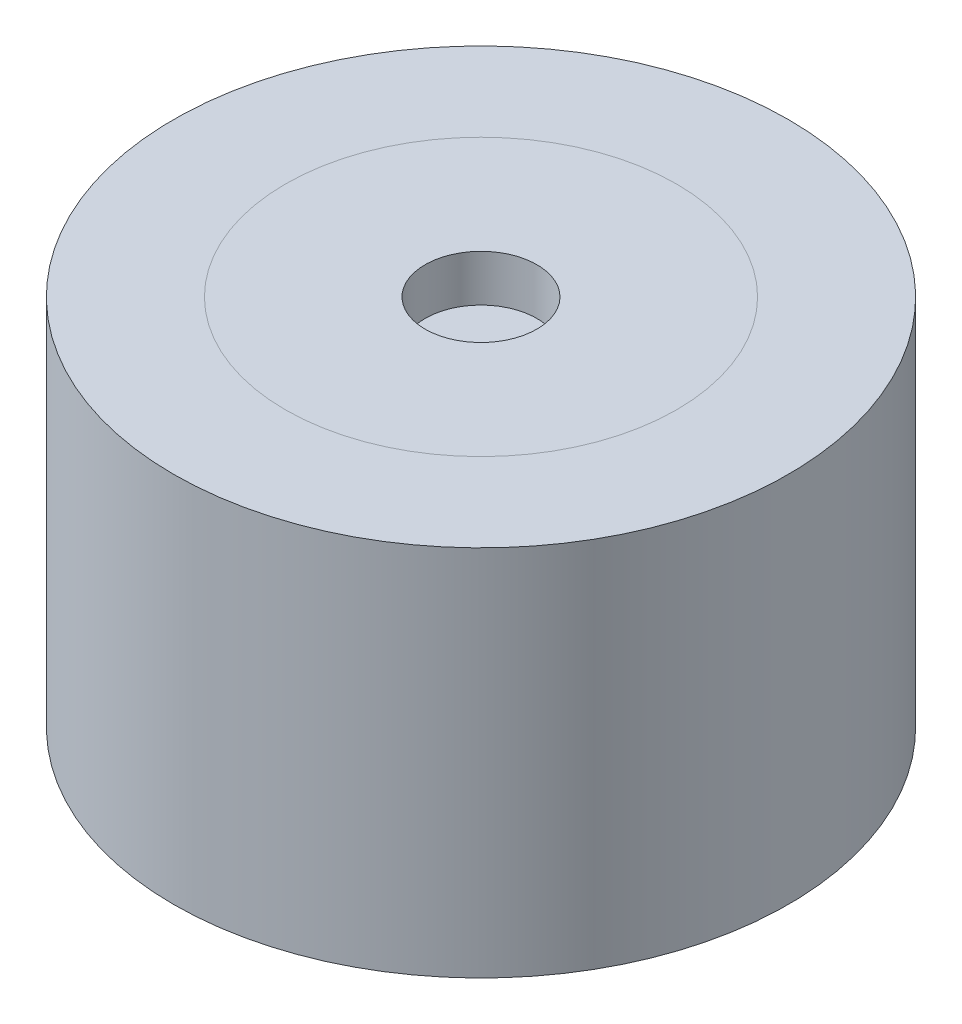
SolidWorks part; units mm, degrees
ref_plane "前视基准面" through (0, 0, 0) normal (0, 0, 1) x (1, 0, 0)
ref_plane "上视基准面" through (0, 0, 0) normal (0, 1, 0) x (1, 0, 0)
ref_plane "右视基准面" through (0, 0, 0) normal (1, 0, 0) x (0, 0, -1)
sketch "草图1" plane through (0, 0, 0) normal (0, 1, 0) x (1, 0, 0)
  circle A0 centre (0, 0) radius 33
extrude "凸台-拉伸1" add sketch "草图1" along normal blind 40
sketch "草图2" plane through (0, 40, 0) normal (0, 1, 0) x (1, 0, 0)
  circle A0 centre (0, 0) radius 6
extrude "切除-拉伸1" cut sketch "草图2" against normal blind 5
sketch "草图3" plane through (0, 0, 0) normal (0, -1, 0) x (1, 0, 0)
  circle A0 centre (0, 0) radius 21
  dimension "D1" = 42
split "分割1" trim tools "草图3" bodies to split 107 resulting bodies 108 109
